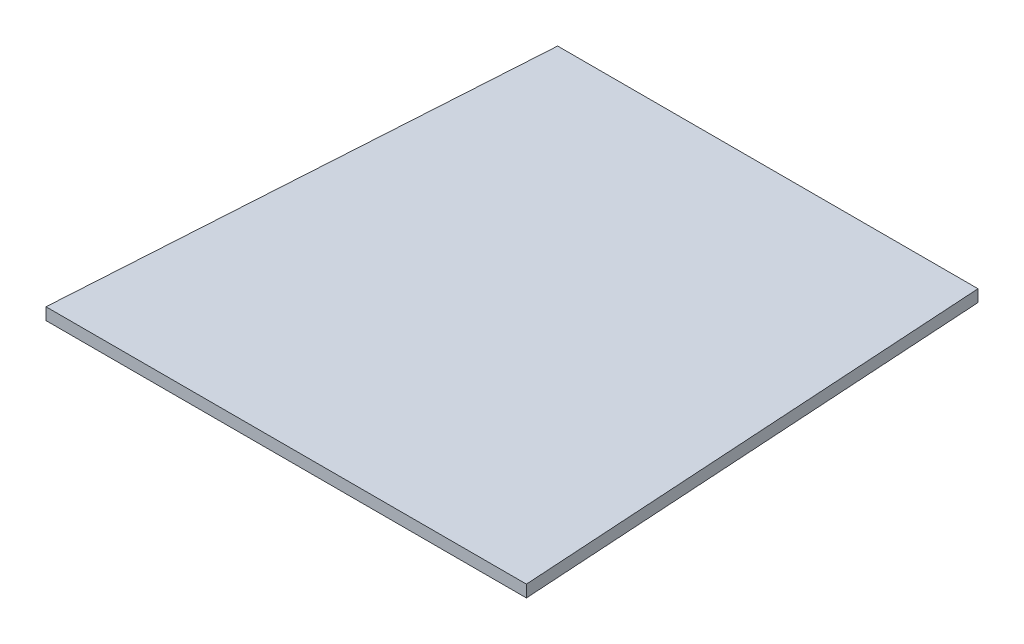
SolidWorks part; units mm, degrees
ref_plane "Płaszczyzna przednia" through (0, 0, 0) normal (0, 0, 1) x (1, 0, 0)
ref_plane "Płaszczyzna górna" through (0, 0, 0) normal (0, 1, 0) x (1, 0, 0)
ref_plane "Płaszczyzna prawa" through (0, 0, 0) normal (1, 0, 0) x (0, 0, -1)
sketch "Szkic1" plane through (0, 0, 0) normal (0, 1, 0) x (1, 0, 0)
  line L0 (-200, -138.961) -> (-175, 262.039)
  line L1 (-175, 262.039) -> (175, 262.039)
  line L2 (175, 262.039) -> (200, -138.961)
  line L3 (200, -138.961) -> (-200, -138.961)
  point P2 (0, -138.961)
  point P5 (0, 262.039)
  point P7 (-187.5, 61.539)
  point P8 (187.5, 61.539)
  dimension "D1" = 400
  dimension "D2" = 401
  dimension "D3" = 401
  dimension "D4" = 350
  dimension "D5" = 138.961
extrude "Dodanie-wyciągnięcie1" add sketch "Szkic1" along normal blind 10
